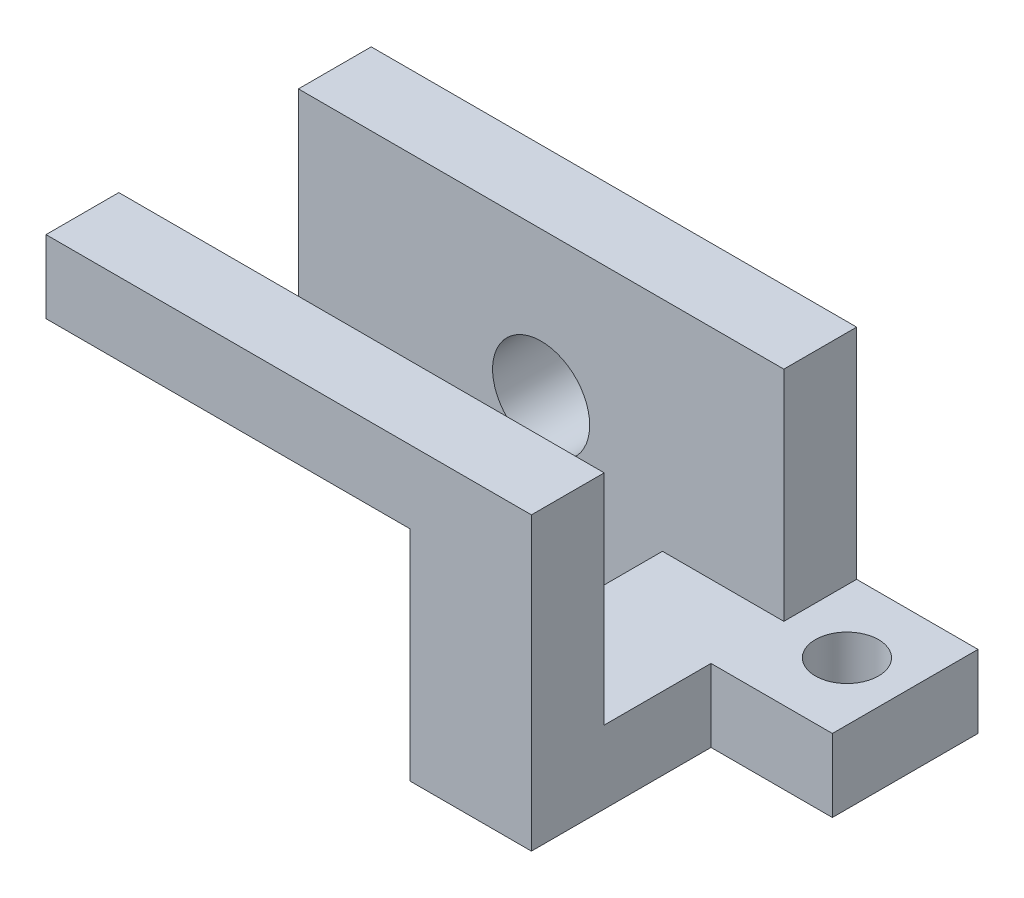
SolidWorks part; units mm, degrees
ref_plane "Płaszczyzna przednia" through (0, 0, 0) normal (0, 0, 1) x (1, 0, 0)
ref_plane "Płaszczyzna górna" through (0, 0, 0) normal (0, 1, 0) x (1, 0, 0)
ref_plane "Płaszczyzna prawa" through (0, 0, 0) normal (1, 0, 0) x (0, 0, -1)
sketch "Szkic1" plane through (0, 0, 0) normal (0, 0, 1) x (1, 0, 0)
  line L1 (-50, 30) -> (50, 30)
  line L2 (-50, 30) -> (-50, -30)
  line L3 (-50, -30) -> (50, -30)
  line L4 (50, 30) -> (50, -30)
  line L5 (-50, 30) -> (50, -30) construction
  line L6 (-50, -30) -> (50, 30) construction
  circle A0 centre (0, 0) radius 10
  point P0 (0, 0)
  dimension "D2" = 20
  dimension "D1" = 60
  dimension "D3" = 100
extrude "Dodanie-wyciągnięcie1" add sketch "Szkic1" against normal blind 15
ref_plane "Płaszczyzna1" through (0, 0, 37) normal (0, 0, 1) x (1, 0, 0)
sketch "Szkic2" plane through (0, 0, 37) normal (0, 0, 1) x (1, 0, 0)
  line L0 (-50, 30) -> (-50, 15)
  line L1 (-50, 30) -> (-50, -30) construction
  line L2 (-50, 15) -> (25, 15)
  line L3 (25, 15) -> (25, -30)
  line L4 (-50, -30) -> (50, -30) construction
  line L5 (25, -30) -> (50, -30)
  line L6 (50, -30) -> (50, 30)
  line L7 (50, 30) -> (-50, 30)
  dimension "D1" = 15
  dimension "D2" = 25
extrude "Dodanie-wyciągnięcie2" add sketch "Szkic2" along normal blind 15 separate body
ref_plane "Płaszczyzna2" through (0, -30, 0) normal (0, -1, 0) x (-1, 0, 0)
sketch "Szkic3" plane through (0, -30, 0) normal (0, -1, 0) x (-1, 0, 0)
  line L0 (-25, 0) -> (-25, -37)
  line L1 (50, 0) -> (-50, 0) construction
  line L2 (-25, -37) -> (-50, -37) construction
  line L3 (-25, -37) -> (-50, -37)
  line L4 (-50, -37) -> (-50, -15)
  line L5 (-50, -15) -> (-75, -15)
  line L6 (-75, -15) -> (-75, 15)
  line L7 (-75, 15) -> (-50, 15)
  line L8 (-50, 15) -> (-50, 0)
  line L9 (-50, 0) -> (-25, 0)
  circle A0 centre (-63, 0) radius 6.5
  point P17 (0, 0)
  point P19 (0, 0)
  dimension "D3" = 13
  dimension "D1" = 30
  dimension "D2" = 50
  dimension "D4" = 12
extrude "Dodanie-wyciągnięcie5" add sketch "Szkic3" against normal blind 15
